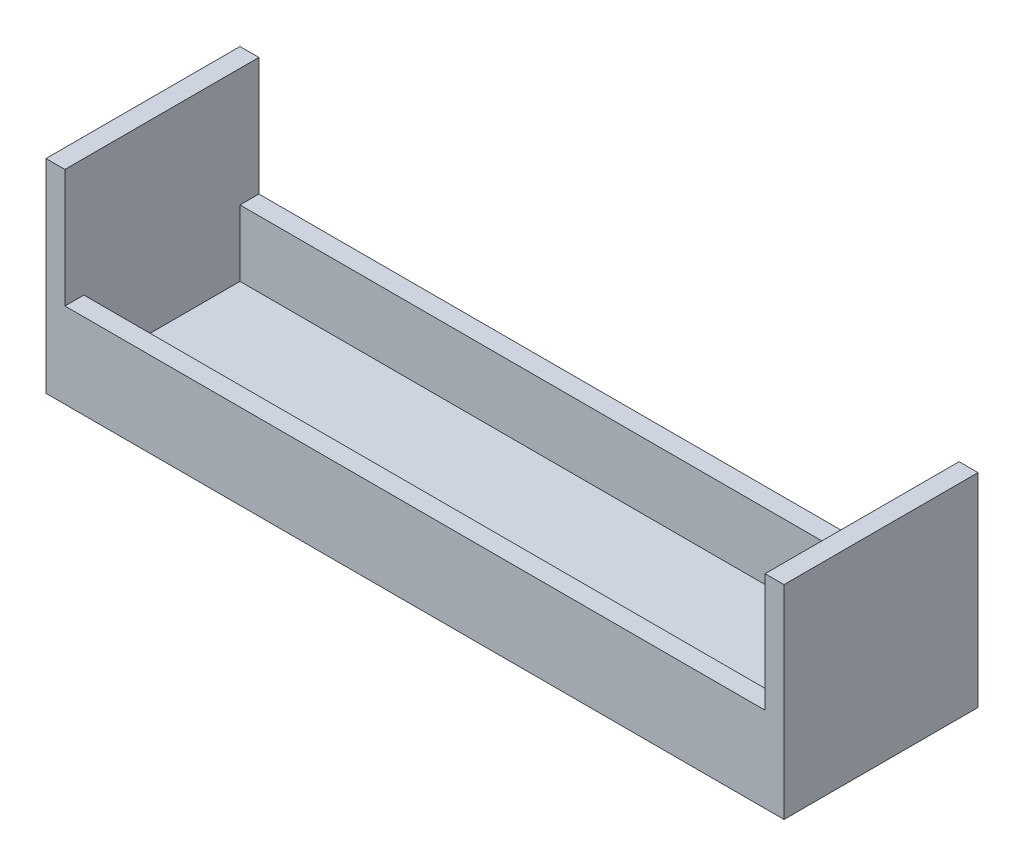
SolidWorks part; units mm, degrees
ref_plane "Alzado" through (0, 0, 0) normal (0, 0, 1) x (1, 0, 0)
ref_plane "Planta" through (0, 0, 0) normal (0, 1, 0) x (1, 0, 0)
ref_plane "Vista lateral" through (0, 0, 0) normal (1, 0, 0) x (0, 0, -1)
sketch "Croquis1" plane through (0, 0, 0) normal (0, 1, 0) x (1, 0, 0)
  line L1 (-39, -10.25) -> (39, -10.25)
  line L2 (-39, -10.25) -> (-39, 10.25)
  line L3 (-39, 10.25) -> (39, 10.25)
  line L4 (39, -10.25) -> (39, 10.25)
  line L5 (-39, -10.25) -> (39, 10.25) construction
  line L6 (-39, 10.25) -> (39, -10.25) construction
  point P0 (0, 0)
  dimension "D1" = 20.5
  dimension "D2" = 78
extrude "Saliente-Extruir1" add sketch "Croquis1" along normal blind 21.5
shell "Vaciado1" thickness 2
sketch "Croquis2" plane through (0, 0, 10.25) normal (0, 0, 1) x (1, 0, 0)
  line L0 (37, 21.5) -> (37, 2) construction
  line L1 (-37, 21.5) -> (37, 21.5)
  line L2 (-37, 21.5) -> (-37, 9)
  line L3 (-37, 9) -> (37, 9)
  line L4 (37, 21.5) -> (37, 9)
  dimension "D1" = 12.5
extrude "Cortar-Extruir1" cut sketch "Croquis2" against normal blind 41.5
